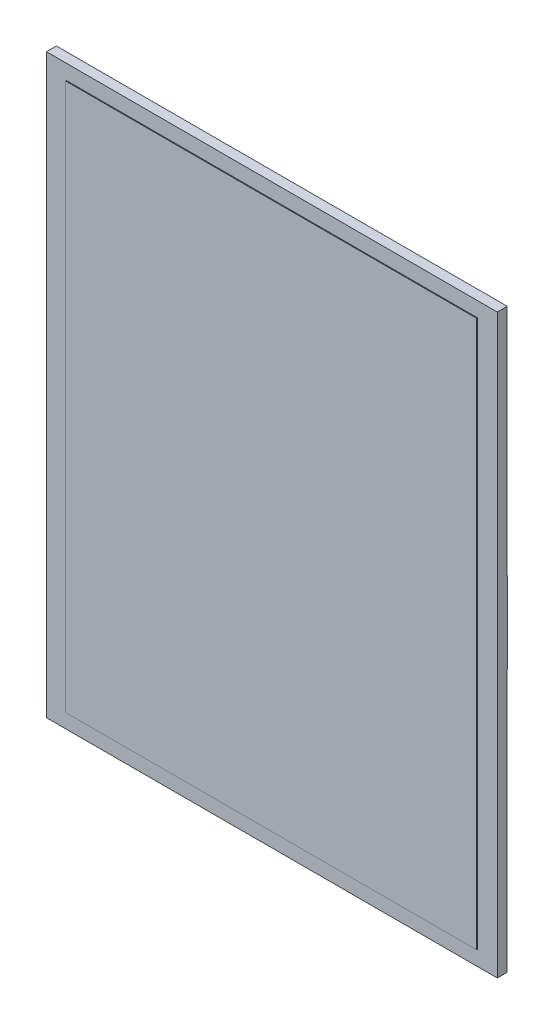
SolidWorks part; units mm, degrees
ref_plane "Front Plane" through (0, 0, 0) normal (0, 0, 1) x (1, 0, 0)
ref_plane "Top Plane" through (0, 0, 0) normal (0, 1, 0) x (1, 0, 0)
ref_plane "Right Plane" through (0, 0, 0) normal (1, 0, 0) x (0, 0, -1)
sketch "Sketch1" plane through (0, 0, 0) normal (0, 0, 1) x (1, 0, 0)
  line L0 (-68, -87) -> (68, -87)
  line L1 (-68, -87) -> (-68, 87)
  line L2 (68, -87) -> (68, 87)
  line L3 (-68, 87) -> (68, 87)
  line L4 (-68, -87) -> (68, 87) construction
  line L5 (68, -87) -> (-68, 87) construction
  point P1 (0, 0)
  dimension "D1" = 136
  dimension "D2" = 174
extrude "Boss-Extrude1" add sketch "Sketch1" along normal blind 3
sketch "Sketch2" plane through (0, 0, 3) normal (0, 0, 1) x (1, 0, 0)
  line L0 (-62, -82.5) -> (62, -82.5)
  line L1 (-62, -82.5) -> (-62, 82.5)
  line L2 (62, -82.5) -> (62, 82.5)
  line L3 (-62, 82.5) -> (62, 82.5)
  line L4 (-62, -82.5) -> (62, 82.5) construction
  line L5 (62, -82.5) -> (-62, 82.5) construction
  point P1 (0, 0)
  dimension "D1" = 124
  dimension "D2" = 165
extrude "Boss-Extrude2" add sketch "Sketch2" along normal blind 0.25
sketch "Sketch3" plane through (0, 0, 0) normal (0, 0, -1) x (-1, 0, 0)
  line L0 (-68, 16.5833) -> (-68, -7.9172)
  line L1 (-68, 16.5833) -> (-49.8446, 16.5833)
  line L2 (-68, -7.9172) -> (-49.8446, -7.9172)
  line L3 (-49.8446, 16.5833) -> (-49.8446, -7.9172)
  line L4 (-68, -87) -> (-68, 87) construction
extrude "Boss-Extrude3" add sketch "Sketch3" along normal blind 0.1
